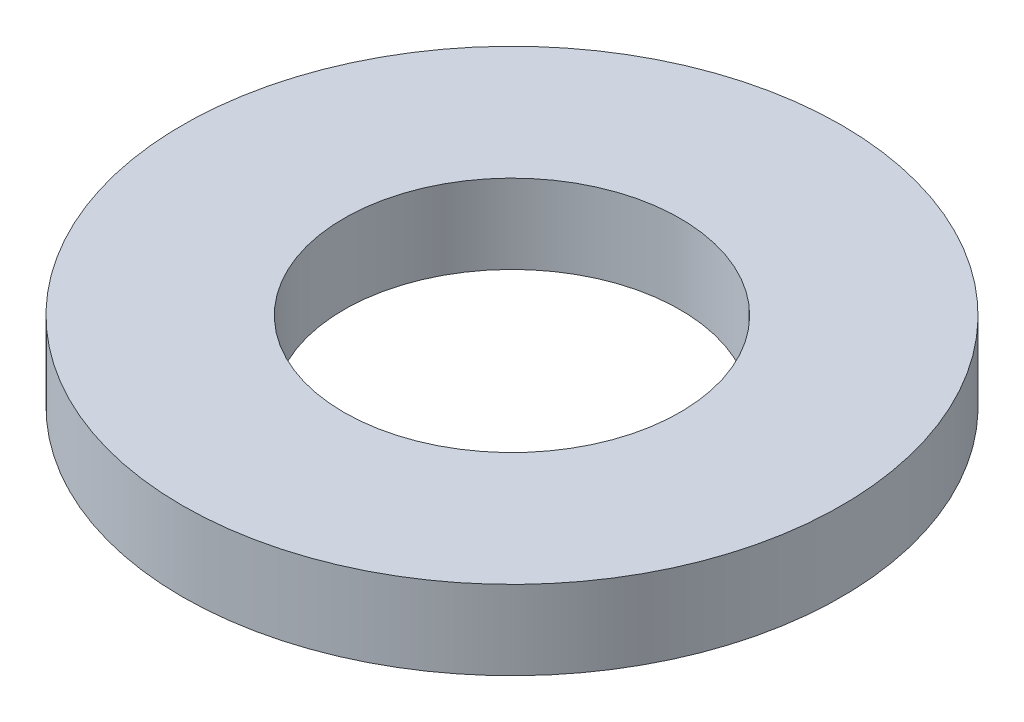
SolidWorks part; units mm, degrees
material "ABS"
ref_plane "Front Plane" through (0, 0, 0) normal (0, 0, 1) x (1, 0, 0)
ref_plane "Top Plane" through (0, 0, 0) normal (0, 1, 0) x (1, 0, 0)
ref_plane "Right Plane" through (0, 0, 0) normal (1, 0, 0) x (0, 0, -1)
sketch "Sketch1" plane through (0, 0, 0) normal (0, 1, 0) x (1, 0, 0)
  circle A0 centre (0, 0) radius 5
  dimension "D1" = 10
extrude "Boss-Extrude1" add sketch "Sketch1" along normal blind 1.2
sketch "Sketch2" plane through (0, 1.2, 0) normal (0, 1, 0) x (1, 0, 0)
  circle A0 centre (0, 0) radius 2.55
  dimension "D1" = 5.1
extrude "Cut-Extrude1" cut sketch "Sketch2" against normal blind 1.2
